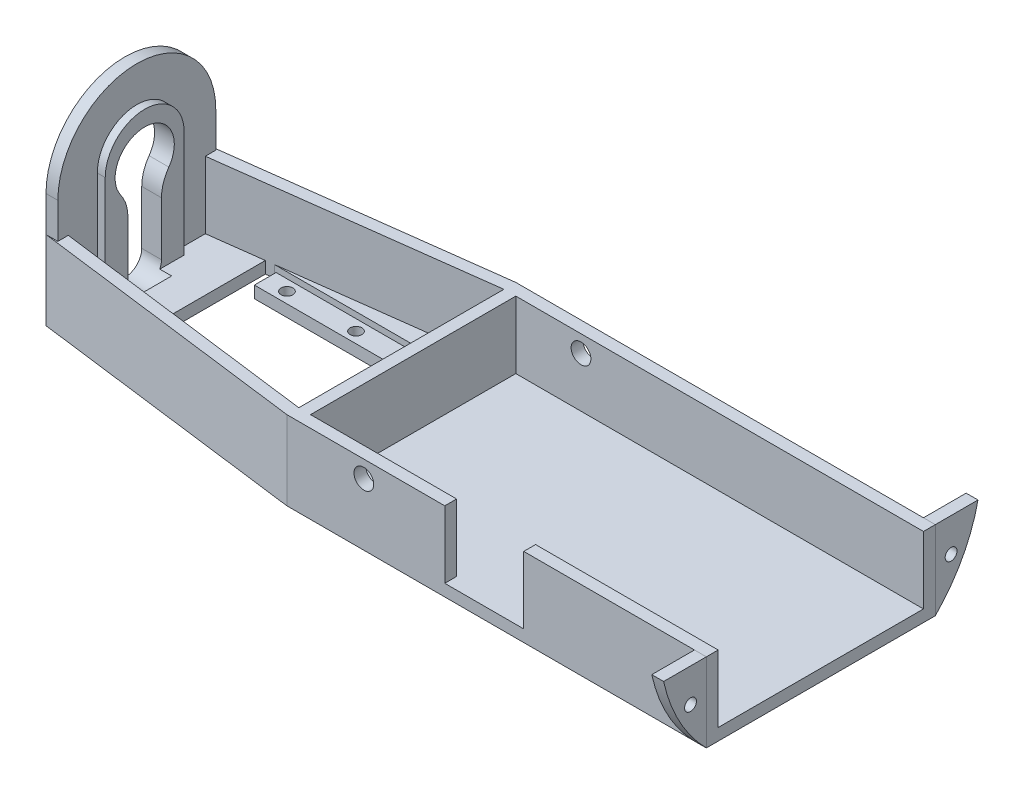
SolidWorks part; units mm, degrees
ref_plane "Front Plane" through (0, 0, 0) normal (0, 0, 1) x (1, 0, 0)
ref_plane "Top Plane" through (0, 0, 0) normal (0, 1, 0) x (1, 0, 0)
ref_plane "Right Plane" through (0, 0, 0) normal (1, 0, 0) x (0, 0, -1)
sketch "Sketch2" plane through (0, 0, 0) normal (0, 1, 0) x (1, 0, 0)
  line L0 (-119.25, 20) -> (-119.25, -20)
  line L1 (-49.25, -29) -> (57, -29)
  line L2 (-49.25, -29) -> (-49.25, 29)
  line L3 (-49.25, 29) -> (57, 29)
  line L4 (57, -29) -> (57, 29)
  line L6 (60, 12) -> (60, -39) construction
  line L7 (-119.25, -20) -> (-49.25, -29)
  line L8 (-119.25, 20) -> (-49.25, 29)
  line L9 (-46.25, -23.4) -> (-46.25, 23.4) construction
  line L10 (-46.25, 23.4) -> (-46.25, -23.4) construction
  point P0 (0, 0)
  point P8 (-49.25, 0)
  point P9 (-119.25, 0)
  point P14 (-46.25, 0)
  dimension "D1" = 3
  dimension "D2" = 58
  dimension "D3" = 40
  dimension "D4" = 70
  dimension "D5" = 3
extrude "Boss-Extrude1" add sketch "Sketch2" along normal blind 3 contours L8 L0 L7 L2 | L1 L4 L3 L2
sketch "Sketch3" plane through (0, 0, 0) normal (0, -1, 0) x (1, 0, 0)
  line L0 (-49.25, -29) -> (57, -29) construction
  line L1 (-49.25, 29) -> (-46.25, 29)
  line L2 (-49.25, 29) -> (-49.25, -29)
  line L3 (-49.25, -29) -> (-46.25, -29)
  line L4 (-46.25, 29) -> (-46.25, -29)
  line L5 (57, 29) -> (57, -29) construction
  line L6 (-46.25, 29) -> (57, 29)
  line L7 (-46.25, 29) -> (-46.25, 26)
  line L8 (-46.25, 26) -> (57, 26)
  line L9 (57, 29) -> (57, 26)
  line L10 (-119.25, 20) -> (-49.25, 29) construction
  line L11 (57, -29) -> (-46.25, -29)
  line L12 (57, -29) -> (57, -26)
  line L13 (57, -26) -> (-46.25, -26)
  line L14 (-46.25, -29) -> (-46.25, -26)
  line L15 (-119.25, -16.9753) -> (-49.25, -25.9753)
  line L16 (-119.25, -20) -> (-49.25, -29) construction
  line L17 (-119.25, -20) -> (-119.25, 20) construction
  line L18 (-119.25, 16.9753) -> (-119.25, 20)
  line L19 (-119.25, 20) -> (-49.25, 29)
  line L20 (-49.25, 29) -> (-49.25, 25.9753)
  line L21 (-119.25, -16.9753) -> (-119.25, -20)
  line L22 (-119.25, -20) -> (-49.25, -29)
  line L23 (-49.25, -25.9753) -> (-49.25, -29)
  line L29 (-119.25, 16.9753) -> (-49.25, 25.9753)
  line M3 (-49.25, -29) -> (57, -29)
  line M4 (57, -29) -> (57, 29)
  line M5 (57, 29) -> (-49.25, 29)
  dimension "D1" = 3
  dimension "D2" = 3
  dimension "D3" = 3
  dimension "D4" = 3
  dimension "D5" = 3
extrude "Boss-Extrude2" add sketch "Sketch3" against normal blind 20 contours L4 L8 M4 M5 | L4 L2 M5 M3 | L13 L4 M4 M3
sketch "Sketch4" plane through (0, 0, 0) normal (0, -1, 0) x (1, 0, 0)
  line L0 (-119.25, -20) -> (-119.25, 20)
  line L1 (-119.25, -20) -> (-116.25, -20)
  line L2 (-119.25, 20) -> (-116.25, 20)
  line L3 (-116.25, -20) -> (-116.25, 20)
  dimension "D1" = 3
extrude "Boss-Extrude3" add sketch "Sketch4" against normal blind 29
sketch "Sketch5" plane through (0, 3, 0) normal (0, 1, 0) x (1, 0, 0)
  line L0 (-49.25, 25.9753) -> (-116.25, 17.361)
  line L1 (-49.25, 29) -> (-49.25, -29) construction
  line L2 (-116.25, -20) -> (-116.25, 20) construction
  line L3 (-116.25, 17.361) -> (-119.25, 20)
  line L4 (-119.25, 20) -> (-49.25, 29)
  line L5 (-49.25, 29) -> (-49.25, 25.9753)
  line L6 (-49.25, -25.9753) -> (-116.25, -17.361)
  line L7 (-116.25, -17.361) -> (-119.25, -20)
  line L8 (-119.25, -20) -> (-49.25, -29)
  line L9 (-49.25, -29) -> (-49.25, -25.9753)
  dimension "D1" = 3
  dimension "D2" = 3
extrude "Boss-Extrude4" add sketch "Sketch5" along normal up to surface (17 mm away) up to face at (4.625, 20, 0)
sketch "Sketch6" plane through (-119.25, 0, 0) normal (-1, 0, 0) x (0, 0, 1)
  line L0 (20, 29) -> (-20, 29) construction
  circle A0 centre (0, 29) radius 20
extrude "Boss-Extrude5" add sketch "Sketch6" against normal up to surface (3 mm away) up to face at (-116.25, 18, 0)
sketch "Sketch7" plane through (-119.25, 0, 0) normal (-1, 0, 0) x (0, 0, 1)
  circle A0 centre (0, 29) radius 3.1
  point P21 (0, 30)
  dimension "D1" = 6.2
sketch "Sketch19" plane through (-116.25, 0, 0) normal (1, 0, 0) x (0, 0, -1)
  line L0 (20, 0) -> (-20, 0) construction
  line L1 (-10, 30) -> (-10, 0)
  line L2 (10, 30) -> (10, 0)
  line L3 (-10, 0) -> (10, 0)
  arc A0 (10, 30) -> (-10, 30) centre (0, 30) ccw
  circle A1 centre (0, 30) radius 1.5
  point P11 (0, 0)
  dimension "D1" = 20
  dimension "D2" = 3
extrude "Boss-Extrude9" add sketch "Sketch19" along normal blind 2
sketch "Sketch10" plane through (0, 0, 29) normal (0, 0, 1) x (1, 0, 0)
  circle A0 centre (-29.74, 15.6975) radius 2.5
  circle A1 centre (-29.74, 15.6975) radius 1.7272 construction
  point P3 (-29.75, 15.5)
  point P4 (0, 0)
  point P5 (-30.2473, 15.6072)
  point P6 (-30.8772, 10.1424)
  dimension "D1" = 5
extrude "Cut-Extrude3" cut sketch "Sketch10" against normal through all both and the other way through all
sketch "Sketch16" plane through (57, 0, 0) normal (1, 0, 0) x (0, 0, -1)
  line L0 (-29, 20) -> (-39.8121, 20)
  line L1 (-29, 0) -> (-29, 20)
  line L2 (29, 20) -> (39.8121, 20)
  line L3 (29, 0) -> (29, 20)
  arc A0 (-39.8121, 20) -> (-29, 0) centre (0, 28.6) ccw
  circle A1 centre (-33, 11.5) radius 1.5 construction
  arc A2 (29, 0) -> (39.8121, 20) centre (0, 28.6) ccw
  circle A3 centre (-33, 11.5) radius 1.5
  arc A4 (-58.5297, 41.8011) -> (58.5297, 41.8011) centre (0, 28.6) ccw construction
  circle A5 centre (33, 11.5) radius 1.5
  circle A7 centre (33, 11.5) radius 1.5 construction
extrude "Boss-Extrude8" add sketch "Sketch16" against normal blind 3 separate body
sketch "Sketch18" plane through (0, 0, 29) normal (0, 0, 1) x (1, 0, 0)
  line L0 (57, 20) -> (-49.25, 20) construction
  line L1 (10.75, 20) -> (-9.25, 20)
  line L2 (10.75, 20) -> (10.75, 3)
  line L3 (10.75, 3) -> (-9.25, 3)
  line L4 (-9.25, 20) -> (-9.25, 3)
  line L5 (10.75, 5.4) -> (10.75, 17.4) construction
  line L6 (-49.25, 0) -> (57, 0) construction
  dimension "D1" = 20
  dimension "D2" = 3
extrude "Cut-Extrude5" cut sketch "Sketch18" against normal up to next (3 mm away)
sketch "Sketch20" plane through (-119.25, 0, 0) normal (-1, 0, 0) x (0, 0, 1)
  line L0 (0, 28.6) -> (0, 4.85)
  line L1 (-4.25, 28.6) -> (-4.25, 4.85)
  line L2 (4.25, 28.6) -> (4.25, 4.85)
  circle A0 centre (0, 28.6) radius 7.5
  arc A1 (-4.25, 28.6) -> (4.25, 28.6) centre (0, 28.6) cw
  arc A2 (-4.25, 4.85) -> (4.25, 4.85) centre (0, 4.85) ccw
  arc A4 (29, 0) -> (39.8121, 20) centre (0, 28.6) ccw construction
  point P12 (-124.7949, 40.6119)
  dimension "D1" = 15
  dimension "D4" = 23.75
  dimension "D2" = 4.25
  dimension "D3" = 4.25
extrude "Cut-Extrude6" cut sketch "Sketch20" against normal blind 8
fillet "Fillet1" radius 10 2 edges at (-116.75, 22.4204, 4.25) (-116.75, 22.4204, -4.25)
sketch "Sketch21" plane through (0, 0, 0) normal (0, -1, 0) x (-1, 0, 0)
  line L1 (100.7812, -12.6909) -> (55.2812, -12.6909)
  line L2 (100.7812, -12.6909) -> (100.7812, 12.3091)
  line L3 (100.7812, 12.3091) -> (55.2812, 12.3091)
  line L4 (55.2812, -12.6909) -> (55.2812, 12.3091)
  circle A0 centre (93.2812, -15.4409) radius 1.5
  circle A1 centre (75.7812, -15.4409) radius 1.5
  circle A2 centre (58.7812, -15.4409) radius 1.5
  circle A3 centre (52.5312, -7.6909) radius 1.5
  circle A4 centre (52.5312, 7.3091) radius 1.5
  circle A5 centre (58.7812, 15.0591) radius 1.5
  circle A6 centre (75.7812, 15.0591) radius 1.5
  circle A7 centre (93.2812, 15.0591) radius 1.5
  circle A8 centre (93.2812, 15.0591) radius 1.5 construction
  circle A9 centre (75.7812, 15.0591) radius 1.5 construction
  circle A10 centre (58.7812, 15.0591) radius 1.5 construction
  circle A11 centre (52.5312, 7.3091) radius 1.5 construction
  circle A12 centre (52.5312, -7.6909) radius 1.5 construction
  circle A13 centre (58.7812, -15.4409) radius 1.5 construction
  circle A14 centre (75.7812, -15.4409) radius 1.5 construction
  circle A15 centre (93.2812, -15.4409) radius 1.5 construction
extrude "Cut-Extrude7" cut sketch "Sketch21" against normal up to next (3 mm away)
ref_plane "Plane1" through (-100.7812, 3, -12.3091) normal (0, 0, -1) x (-1, 0, 0)
sketch "Sketch23" plane through (0, 3, 0) normal (0, 1, 0) x (1, 0, 0)
  line L0 (-100.7812, -0.1909) -> (-55.2812, -0.1909) construction
  line L1 (-100.7812, -12.6909) -> (-100.7812, 12.3091) construction
  line L2 (-55.2812, 12.3091) -> (-55.2812, -12.6909) construction
  line L3 (-49.25, 25.9753) -> (-49.25, -25.9753) construction
  line L4 (-100.7812, 12.3091) -> (-98.7812, 12.3091)
  line L5 (-100.7812, 12.3091) -> (-100.7812, 17.8091)
  line L6 (-100.7812, 17.8091) -> (-98.7812, 17.8091)
  line L7 (-98.7812, 12.3091) -> (-98.7812, 17.8091)
  line L8 (-100.7812, 17.8091) -> (-49.25, 17.8091)
  line L9 (-100.7812, 17.8091) -> (-100.7812, 19.3499)
  line L10 (-100.7812, 19.3499) -> (-49.25, 19.3499)
  line L11 (-49.25, 17.8091) -> (-49.25, 19.3499)
  line L12 (-116.25, 17.361) -> (-49.25, 25.9753) construction
  line L13 (-100.7812, -12.6909) -> (-98.7812, -12.6909)
  line L14 (-100.7812, -18.1909) -> (-100.7812, -19.7317)
  line L15 (-100.7812, -12.6909) -> (-100.7812, -18.1909)
  line L16 (-98.7812, -12.6909) -> (-98.7812, -18.1909)
  line L17 (-100.7812, -18.1909) -> (-49.25, -18.1909)
  line L18 (-100.7812, -19.7317) -> (-49.25, -19.7317)
  line L19 (-49.25, -18.1909) -> (-49.25, -19.7317)
  point P16 (0, 0)
  line M19 (-100.7812, 12.3091) -> (-55.2812, 12.3091)
  line M21 (-55.2812, -12.6909) -> (-100.7812, -12.6909)
  line M29 (-49.25, -25.9753) -> (-49.25, 25.9753)
  dimension "D1" = 5.5
  dimension "D2" = 2
extrude "Cut-Extrude8" cut sketch "Sketch23" against normal up to next (3 mm away) contours L7 L6 L5 M19 | L10 L9 L6 L8 M29 | L15 L17 L16 M21
sketch "Sketch24" plane through (0, 3, 0) normal (0, 1, 0) x (1, 0, 0)
  line L0 (-100.7812, 19.3499) -> (-100.7812, -19.3499)
  line L1 (-100.7812, -19.3499) -> (-102.7812, -19.0927)
  line L2 (-100.7812, -19.3499) -> (-116.25, -17.361) construction
  line L3 (-102.7812, -19.0927) -> (-102.7812, 19.0927)
  line L4 (-116.25, 17.361) -> (-100.7812, 19.3499) construction
  line L5 (-102.7812, 19.0927) -> (-100.7812, 19.3499)
  dimension "D1" = 2
extrude "Cut-Extrude9" cut sketch "Sketch24" against normal up to next (3 mm away)
